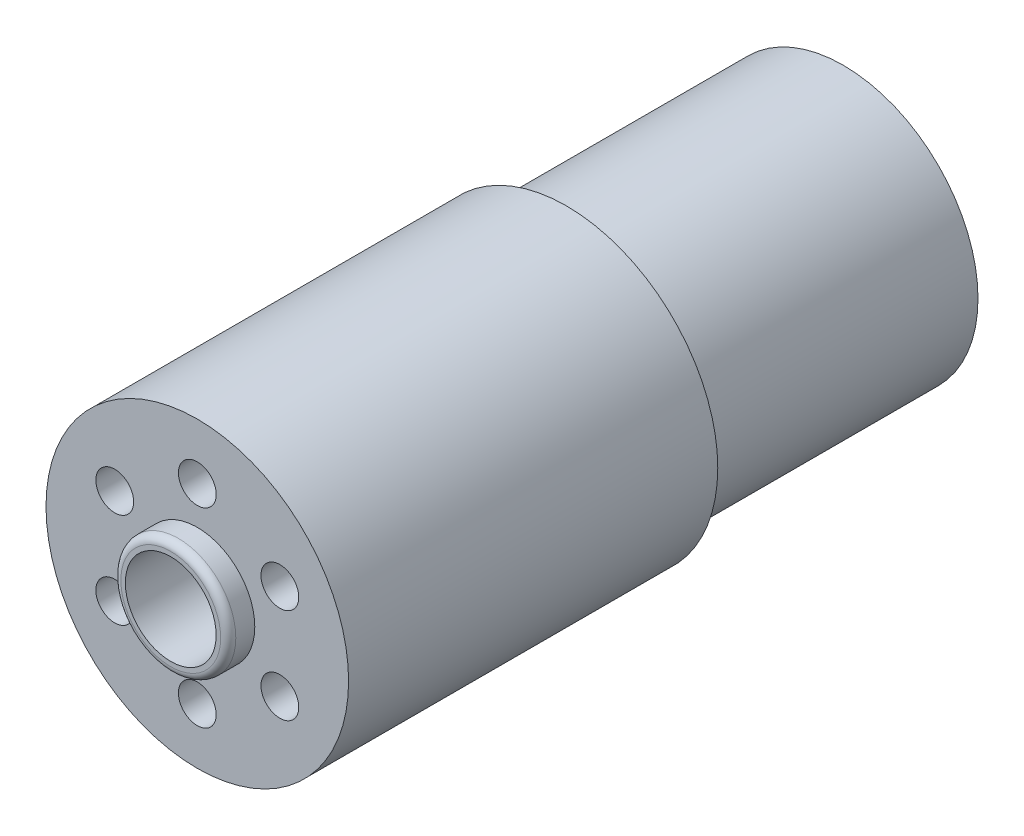
SolidWorks part; units mm, degrees
ref_plane "Front Plane" through (0, 0, 0) normal (0, 0, 1) x (1, 0, 0)
ref_plane "Top Plane" through (0, 0, 0) normal (0, 1, 0) x (1, 0, 0)
ref_plane "Right Plane" through (0, 0, 0) normal (1, 0, 0) x (0, 0, -1)
sketch "Sketch1" plane through (0, 0, 0) normal (0, 0, 1) x (1, 0, 0)
  circle A0 centre (0, 0) radius 25.4
  circle A8 centre (0, 0) radius 9.3953
  point P19 (0, 0)
  dimension "D1" = 50.8
  dimension "D2" = 16.0047
extrude "Boss-Extrude2" add sketch "Sketch1" along normal blind 108.458 contours A0
sketch "Sketch6" plane through (0, 0, 0) normal (0, 0, -1) x (-1, 0, 0)
  circle A0 centre (0, 0) radius 7.62
  circle A1 centre (-13.8581, 8.001) radius 3.175
  circle A2 centre (0, 16.002) radius 3.175
  circle A3 centre (13.8581, 8.001) radius 3.175
  circle A4 centre (13.8581, -8.001) radius 3.175
  circle A5 centre (0, -16.002) radius 3.175
  circle A6 centre (-13.8581, -8.001) radius 3.175
  point P5 (13.2757, 1.2701)
  point P6 (0, 0)
  point P7 (0, 0)
  point P18 (0, 0)
  point P19 (0, 16.002)
  dimension "D1" = 15.24
  dimension "D2" = 6.35
  dimension "D3" = 16.002
  dimension "D4" = 6
extrude "Cut-Extrude1" cut sketch "Sketch6" against normal blind 108.458
sketch "Sketch7" plane through (0, 0, 0) normal (0, 0, -1) x (-1, 0, 0)
  circle A0 centre (0, 0) radius 22.606
  circle A1 centre (0, 0) radius 25.4 construction
  circle A2 centre (0, 0) radius 25.4
  point P6 (0, 0)
  dimension "D1" = 2.794
extrude "Cut-Extrude2" cut sketch "Sketch7" against normal blind 46.482
sketch "Sketch8" plane through (0, 0, 108.458) normal (0, 0, 1) x (1, 0, 0)
  circle A0 centre (0, 0) radius 7.62
  circle A1 centre (0, 0) radius 9.652
  dimension "D1" = 2.032
extrude "Boss-Extrude7" add sketch "Sketch8" along normal blind 4.4577
sketch "Sketch9" plane through (0, 0, 0) normal (0, 0, -1) x (-1, 0, 0)
  circle A0 centre (0, 0) radius 7.62
  circle A1 centre (0, 0) radius 9.652
  dimension "D1" = 2.032
extrude "Boss-Extrude8" add sketch "Sketch9" along normal blind 4.4577
fillet "Fillet1" radius 1.27 2 edges at (9.652, 0, 112.9157) (-9.652, 0, -4.4577)
